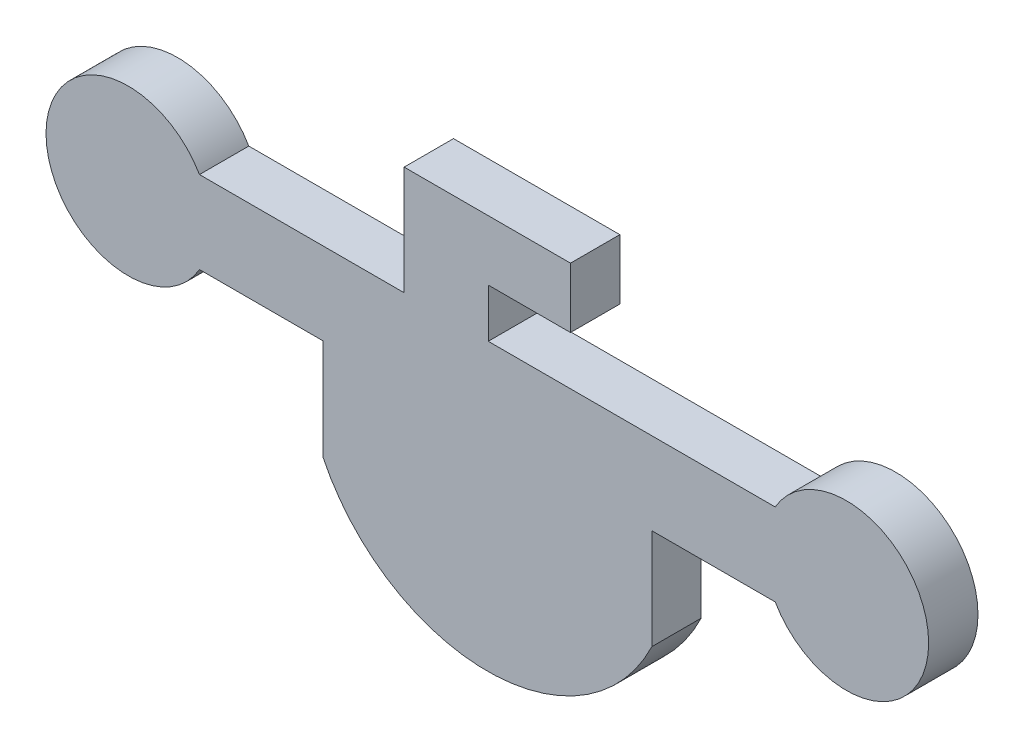
SolidWorks part; units mm, degrees
ref_plane "Front" through (0, 0, 0) normal (0, 0, 1) x (1, 0, 0)
ref_plane "Top" through (0, 0, 0) normal (0, 1, 0) x (1, 0, 0)
ref_plane "Right" through (0, 0, 0) normal (1, 0, 0) x (0, 0, -1)
sketch "Sketch1" plane through (0, 0, 0) normal (0, 0, 1) x (1, 0, 0)
  line L0 (-1351.2802, 100.5151) -> (-1341.1669, 100.5151)
  line L1 (-1341.1669, 96.8611) -> (-1346.1669, 96.8611)
  line L2 (-1328.7235, 93.8998) -> (-1346.1669, 93.8998)
  line L3 (-1336.2235, 88.8998) -> (-1328.7235, 88.8998)
  line L4 (-1363.7235, 88.8998) -> (-1356.2235, 88.8998)
  line L5 (-1363.7235, 93.8998) -> (-1351.2802, 93.8998)
  line L6 (-1336.2235, 82.7934) -> (-1336.2235, 88.8998)
  line L7 (-1356.2235, 82.7934) -> (-1356.2235, 88.8998)
  line L11 (-1346.1669, 96.8611) -> (-1346.1669, 93.8998)
  line L12 (-1351.2802, 93.8998) -> (-1351.2802, 100.5151)
  line L13 (-1341.1669, 100.5151) -> (-1341.1669, 96.8611)
  line L14 (-1346.2235, 100.5151) -> (-1346.2235, 72.3338) construction
  arc A0 (-1328.7235, 93.8998) -> (-1328.7235, 88.8998) centre (-1324.3934, 91.3998) cw
  arc A2 (-1356.2235, 82.7934) -> (-1336.2235, 82.7934) centre (-1346.2235, 87.5994) ccw
  arc A3 (-1363.7235, 93.8998) -> (-1363.7235, 88.8998) centre (-1368.0537, 91.3998) ccw
  dimension "D5" = 5
  dimension "D1" = 35
  dimension "D2" = 20
  dimension "D3" = 5
  dimension "D4" = 2.5
  dimension "D6" = 7.5
  dimension "D8" = 5
extrude "Base-Extrude" add sketch "Sketch1" along normal blind 3
